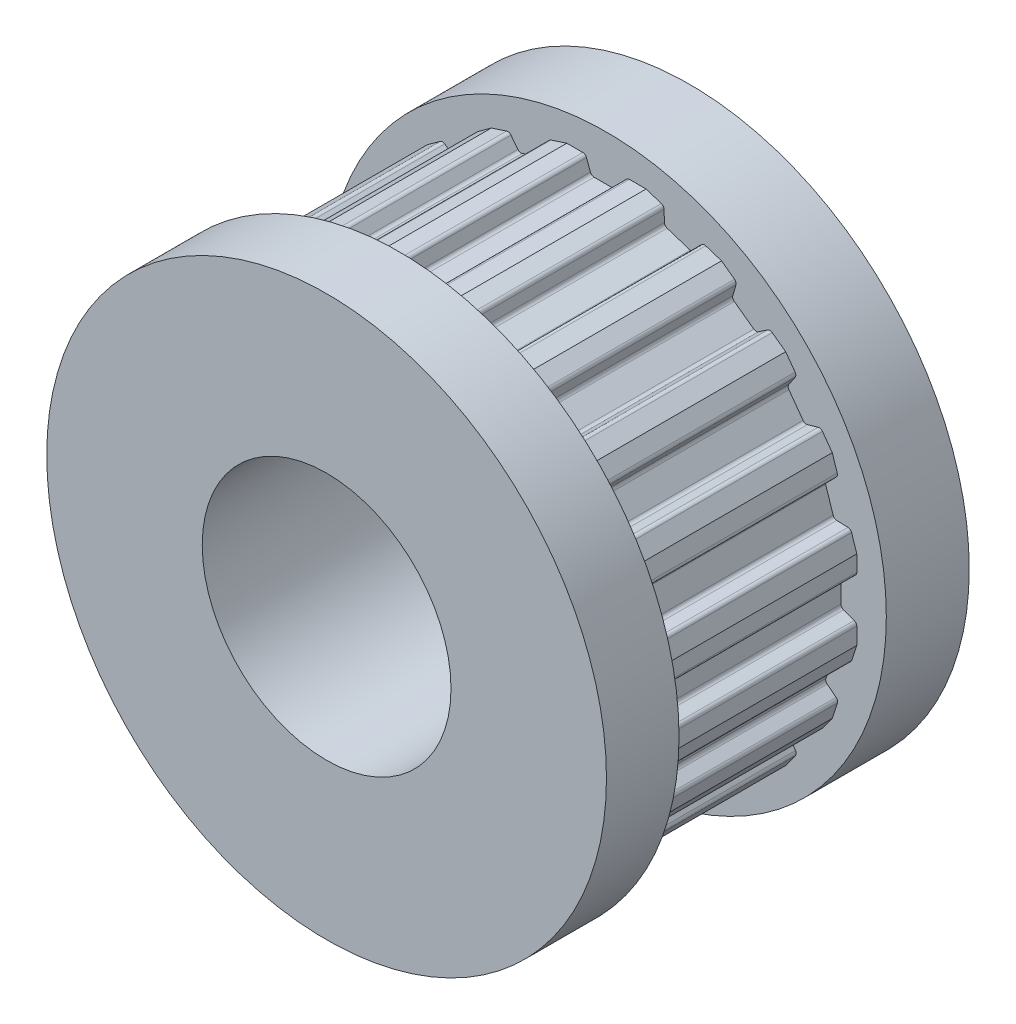
SolidWorks part; units mm, degrees
ref_plane "Front Plane" through (0, 0, 0) normal (0, 0, 1) x (1, 0, 0)
ref_plane "Top Plane" through (0, 0, 0) normal (0, 1, 0) x (1, 0, 0)
ref_plane "Right Plane" through (0, 0, 0) normal (1, 0, 0) x (0, 0, -1)
sketch "Sketch1" plane through (0, 0, 0) normal (0, 0, 1) x (1, 0, 0)
  line L0 (-50.7402, 0.3127) -> (-50.3387, 0.3127)
  line L5 (-50.2492, 0.3754) -> (-50.1561, 0.631)
  line L6 (-50.0666, 0.6937) -> (-49.4855, 0.6937)
  line L7 (-49.7761, 0.6937) -> (-49.7761, 0) construction
  line L8 (-49.3029, 0.3754) -> (-49.396, 0.631)
  line L39 (-51.1727, 0.5191) -> (-51.1822, 0.791)
  line L40 (-50.2492, 0.3754) -> (-49.3029, 0.3754) construction
  line L56 (-49.2134, 0.3127) -> (-48.8278, 0.3127)
  line L60 (-51.8007, 1.0579) -> (-51.248, 0.8783)
  line L61 (-52.0727, 0.8116) -> (-51.9052, 1.0259)
  line L62 (-52.559, 0.9037) -> (-52.1772, 0.7796)
  line L63 (-51.107, 0.4319) -> (-50.7402, 0.3127)
  line L64 (-52.9066, 1.2337) -> (-52.8316, 1.4952)
  line L65 (-53.3373, 1.9401) -> (-52.8672, 1.5985)
  line L66 (-53.6721, 1.7899) -> (-53.4466, 1.942)
  line L67 (-54.1062, 2.0278) -> (-53.7814, 1.7918)
  line L68 (-52.871, 1.1304) -> (-52.559, 0.9037)
  line L69 (-54.3348, 2.449) -> (-54.1827, 2.6746)
  line L70 (-54.5262, 3.254) -> (-54.1846, 2.7838)
  line L71 (-54.891, 3.2146) -> (-54.6295, 3.2895)
  line L72 (-55.2303, 3.575) -> (-54.9943, 3.2501)
  line L73 (-54.3329, 2.3398) -> (-54.1062, 2.0278)
  line L74 (-55.3175, 4.0462) -> (-55.1031, 4.2137)
  line L75 (-55.2508, 4.8709) -> (-55.0712, 4.3182)
  line L76 (-55.6099, 4.9462) -> (-55.338, 4.9367)
  line L77 (-55.8213, 5.3938) -> (-55.6972, 5.0119)
  line L78 (-55.3495, 3.9417) -> (-55.2303, 3.575)
  line L79 (-55.7586, 5.8689) -> (-55.503, 5.962)
  line L80 (-55.4403, 6.6326) -> (-55.4403, 6.0515)
  line L81 (-55.7586, 6.8152) -> (-55.503, 6.7221)
  line L82 (-55.8213, 7.3062) -> (-55.8213, 6.9047)
  line L83 (-55.8213, 5.7794) -> (-55.8213, 5.3938)
  line L84 (-55.6149, 7.7387) -> (-55.343, 7.7482)
  line L85 (-55.0761, 8.3667) -> (-55.2557, 7.814)
  line L86 (-55.3224, 8.6387) -> (-55.1081, 8.4712)
  line L87 (-55.2303, 9.125) -> (-55.3544, 8.7432)
  line L88 (-55.7021, 7.673) -> (-55.8213, 7.3062)
  line L89 (-54.9003, 9.4726) -> (-54.6388, 9.3976)
  line L90 (-54.1939, 9.9033) -> (-54.5355, 9.4332)
  line L91 (-54.3441, 10.2381) -> (-54.192, 10.0126)
  line L92 (-54.1062, 10.6722) -> (-54.3422, 10.3474)
  line L93 (-55.0036, 9.437) -> (-55.2303, 9.125)
  line L94 (-53.685, 10.9008) -> (-53.4594, 10.7487)
  line L95 (-52.88, 11.0922) -> (-53.3502, 10.7506)
  line L96 (-52.9194, 11.457) -> (-52.8445, 11.1955)
  line L97 (-52.559, 11.7963) -> (-52.8839, 11.5603)
  line L98 (-53.7942, 10.8989) -> (-54.1062, 10.6722)
  line L99 (-52.0878, 11.8835) -> (-51.9203, 11.6691)
  line L100 (-51.2631, 11.8168) -> (-51.8158, 11.6372)
  line L101 (-51.1878, 12.1759) -> (-51.1973, 11.904)
  line L102 (-50.7402, 12.3873) -> (-51.1221, 12.2632)
  line L103 (-52.1923, 11.9155) -> (-52.559, 11.7963)
  line L104 (-50.2651, 12.3246) -> (-50.172, 12.069)
  line L105 (-49.5014, 12.0063) -> (-50.0825, 12.0063)
  line L106 (-49.3188, 12.3246) -> (-49.4119, 12.069)
  line L107 (-48.8278, 12.3873) -> (-49.2293, 12.3873)
  line L108 (-50.3546, 12.3873) -> (-50.7402, 12.3873)
  line L109 (-48.3953, 12.1809) -> (-48.3858, 11.909)
  line L110 (-47.7673, 11.6421) -> (-48.32, 11.8217)
  line L111 (-47.4953, 11.8884) -> (-47.6628, 11.6741)
  line L112 (-47.009, 11.7963) -> (-47.3908, 11.9204)
  line L113 (-48.461, 12.2681) -> (-48.8278, 12.3873)
  line L114 (-46.6614, 11.4663) -> (-46.7364, 11.2048)
  line L115 (-46.2307, 10.7599) -> (-46.7008, 11.1015)
  line L116 (-45.8959, 10.9101) -> (-46.1214, 10.758)
  line L117 (-45.4618, 10.6722) -> (-45.7866, 10.9082)
  line L118 (-46.697, 11.5696) -> (-47.009, 11.7963)
  line L119 (-45.2332, 10.251) -> (-45.3853, 10.0254)
  line L120 (-45.0418, 9.446) -> (-45.3834, 9.9162)
  line L121 (-44.677, 9.4854) -> (-44.9385, 9.4105)
  line L122 (-44.3377, 9.125) -> (-44.5737, 9.4499)
  line L123 (-45.2351, 10.3602) -> (-45.4618, 10.6722)
  line L124 (-44.2505, 8.6538) -> (-44.4649, 8.4863)
  line L125 (-44.3172, 7.8291) -> (-44.4968, 8.3818)
  line L126 (-43.9581, 7.7538) -> (-44.23, 7.7633)
  line L127 (-43.7467, 7.3062) -> (-43.8708, 7.6881)
  line L128 (-44.2185, 8.7583) -> (-44.3377, 9.125)
  line L129 (-43.8094, 6.8311) -> (-44.065, 6.738)
  line L130 (-44.1277, 6.0674) -> (-44.1277, 6.6485)
  line L131 (-43.8094, 5.8848) -> (-44.065, 5.9779)
  line L132 (-43.7467, 5.3938) -> (-43.7467, 5.7953)
  line L133 (-43.7467, 6.9206) -> (-43.7467, 7.3062)
  line L134 (-43.9531, 4.9613) -> (-44.225, 4.9518)
  line L135 (-44.4919, 4.3333) -> (-44.3123, 4.886)
  line L136 (-44.2456, 4.0613) -> (-44.4599, 4.2288)
  line L137 (-44.3377, 3.575) -> (-44.2136, 3.9568)
  line L138 (-43.8659, 5.027) -> (-43.7467, 5.3938)
  line L139 (-44.6677, 3.2274) -> (-44.9292, 3.3024)
  line L140 (-45.3741, 2.7967) -> (-45.0325, 3.2668)
  line L141 (-45.2239, 2.4619) -> (-45.376, 2.6874)
  line L142 (-45.4618, 2.0278) -> (-45.2258, 2.3526)
  line L143 (-44.5644, 3.263) -> (-44.3377, 3.575)
  line L144 (-45.883, 1.7992) -> (-46.1086, 1.9513)
  line L145 (-46.688, 1.6078) -> (-46.2178, 1.9494)
  line L146 (-46.6486, 1.243) -> (-46.7235, 1.5045)
  line L147 (-47.009, 0.9037) -> (-46.6841, 1.1397)
  line L148 (-45.7738, 1.8011) -> (-45.4618, 2.0278)
  line L149 (-47.4802, 0.8165) -> (-47.6477, 1.0309)
  line L150 (-48.3049, 0.8832) -> (-47.7522, 1.0628)
  line L151 (-48.3802, 0.5241) -> (-48.3707, 0.796)
  line L152 (-48.8278, 0.3127) -> (-48.4459, 0.4368)
  line L153 (-47.3757, 0.7845) -> (-47.009, 0.9037)
  arc A0 (-50.3387, 0.3127) -> (-50.2492, 0.3754) centre (-50.3387, 0.408) ccw
  arc A1 (-50.1561, 0.631) -> (-50.0666, 0.6937) centre (-50.0666, 0.5985) cw
  arc A2 (-49.396, 0.631) -> (-49.4855, 0.6937) centre (-49.4855, 0.5985) ccw
  arc A3 (-49.2134, 0.3127) -> (-49.3029, 0.3754) centre (-49.2134, 0.408) cw
  arc A4 (-51.107, 0.4319) -> (-51.1727, 0.5191) centre (-51.0775, 0.5225) cw
  arc A5 (-51.1822, 0.791) -> (-51.248, 0.8783) centre (-51.2774, 0.7877) ccw
  arc A6 (-51.9052, 1.0259) -> (-51.8007, 1.0579) centre (-51.8301, 0.9673) cw
  arc A7 (-52.1772, 0.7796) -> (-52.0727, 0.8116) centre (-52.1477, 0.8702) ccw
  arc A8 (-52.871, 1.1304) -> (-52.9066, 1.2337) centre (-52.815, 1.2074) cw
  arc A9 (-52.8316, 1.4952) -> (-52.8672, 1.5985) centre (-52.9232, 1.5214) ccw
  arc A10 (-53.4466, 1.942) -> (-53.3373, 1.9401) centre (-53.3933, 1.863) cw
  arc A11 (-53.7814, 1.7918) -> (-53.6721, 1.7899) centre (-53.7254, 1.8688) ccw
  arc A12 (-54.3329, 2.3398) -> (-54.3348, 2.449) centre (-54.2558, 2.3958) cw
  arc A13 (-54.1827, 2.6746) -> (-54.1846, 2.7838) centre (-54.2616, 2.7278) ccw
  arc A14 (-54.6295, 3.2895) -> (-54.5262, 3.254) centre (-54.6032, 3.198) cw
  arc A15 (-54.9943, 3.2501) -> (-54.891, 3.2146) centre (-54.9172, 3.3061) ccw
  arc A16 (-55.3495, 3.9417) -> (-55.3175, 4.0462) centre (-55.2589, 3.9712) cw
  arc A17 (-55.1031, 4.2137) -> (-55.0712, 4.3182) centre (-55.1618, 4.2888) ccw
  arc A18 (-55.338, 4.9367) -> (-55.2508, 4.8709) centre (-55.3414, 4.8415) cw
  arc A19 (-55.6972, 5.0119) -> (-55.6099, 4.9462) centre (-55.6066, 5.0414) ccw
  arc A20 (-55.8213, 5.7794) -> (-55.7586, 5.8689) centre (-55.726, 5.7794) cw
  arc A21 (-55.503, 5.962) -> (-55.4403, 6.0515) centre (-55.5355, 6.0515) ccw
  arc A22 (-55.503, 6.7221) -> (-55.4403, 6.6326) centre (-55.5355, 6.6326) cw
  arc A23 (-55.8213, 6.9047) -> (-55.7586, 6.8152) centre (-55.726, 6.9047) ccw
  arc A24 (-55.7021, 7.673) -> (-55.6149, 7.7387) centre (-55.6115, 7.6435) cw
  arc A25 (-55.343, 7.7482) -> (-55.2557, 7.814) centre (-55.3463, 7.8434) ccw
  arc A26 (-55.1081, 8.4712) -> (-55.0761, 8.3667) centre (-55.1667, 8.3961) cw
  arc A27 (-55.3544, 8.7432) -> (-55.3224, 8.6387) centre (-55.2638, 8.7137) ccw
  arc A28 (-55.0036, 9.437) -> (-54.9003, 9.4726) centre (-54.9266, 9.381) cw
  arc A29 (-54.6388, 9.3976) -> (-54.5355, 9.4332) centre (-54.6126, 9.4892) ccw
  arc A30 (-54.192, 10.0126) -> (-54.1939, 9.9033) centre (-54.271, 9.9593) cw
  arc A31 (-54.3422, 10.3474) -> (-54.3441, 10.2381) centre (-54.2652, 10.2914) ccw
  arc A32 (-53.7942, 10.8989) -> (-53.685, 10.9008) centre (-53.7382, 10.8218) cw
  arc A33 (-53.4594, 10.7487) -> (-53.3502, 10.7506) centre (-53.4062, 10.8276) ccw
  arc A34 (-52.8445, 11.1955) -> (-52.88, 11.0922) centre (-52.936, 11.1692) cw
  arc A35 (-52.8839, 11.5603) -> (-52.9194, 11.457) centre (-52.8279, 11.4832) ccw
  arc A36 (-52.1923, 11.9155) -> (-52.0878, 11.8835) centre (-52.1628, 11.8249) cw
  arc A37 (-51.9203, 11.6691) -> (-51.8158, 11.6372) centre (-51.8452, 11.7278) ccw
  arc A38 (-51.1973, 11.904) -> (-51.2631, 11.8168) centre (-51.2925, 11.9074) cw
  arc A39 (-51.1221, 12.2632) -> (-51.1878, 12.1759) centre (-51.0926, 12.1726) ccw
  arc A40 (-50.3546, 12.3873) -> (-50.2651, 12.3246) centre (-50.3546, 12.292) cw
  arc A41 (-50.172, 12.069) -> (-50.0825, 12.0063) centre (-50.0825, 12.1015) ccw
  arc A42 (-49.4119, 12.069) -> (-49.5014, 12.0063) centre (-49.5014, 12.1015) cw
  arc A43 (-49.2293, 12.3873) -> (-49.3188, 12.3246) centre (-49.2293, 12.292) ccw
  arc A44 (-48.461, 12.2681) -> (-48.3953, 12.1809) centre (-48.4905, 12.1775) cw
  arc A45 (-48.3858, 11.909) -> (-48.32, 11.8217) centre (-48.2906, 11.9123) ccw
  arc A46 (-47.6628, 11.6741) -> (-47.7673, 11.6421) centre (-47.7379, 11.7327) cw
  arc A47 (-47.3908, 11.9204) -> (-47.4953, 11.8884) centre (-47.4203, 11.8298) ccw
  arc A48 (-46.697, 11.5696) -> (-46.6614, 11.4663) centre (-46.753, 11.4926) cw
  arc A49 (-46.7364, 11.2048) -> (-46.7008, 11.1015) centre (-46.6448, 11.1786) ccw
  arc A50 (-46.1214, 10.758) -> (-46.2307, 10.7599) centre (-46.1747, 10.837) cw
  arc A51 (-45.7866, 10.9082) -> (-45.8959, 10.9101) centre (-45.8426, 10.8312) ccw
  arc A52 (-45.2351, 10.3602) -> (-45.2332, 10.251) centre (-45.3122, 10.3042) cw
  arc A53 (-45.3853, 10.0254) -> (-45.3834, 9.9162) centre (-45.3064, 9.9722) ccw
  arc A54 (-44.9385, 9.4105) -> (-45.0418, 9.446) centre (-44.9648, 9.502) cw
  arc A55 (-44.5737, 9.4499) -> (-44.677, 9.4854) centre (-44.6508, 9.3939) ccw
  arc A56 (-44.2185, 8.7583) -> (-44.2505, 8.6538) centre (-44.3091, 8.7288) cw
  arc A57 (-44.4649, 8.4863) -> (-44.4968, 8.3818) centre (-44.4062, 8.4112) ccw
  arc A58 (-44.23, 7.7633) -> (-44.3172, 7.8291) centre (-44.2266, 7.8585) cw
  arc A59 (-43.8708, 7.6881) -> (-43.9581, 7.7538) centre (-43.9614, 7.6586) ccw
  arc A60 (-43.7467, 6.9206) -> (-43.8094, 6.8311) centre (-43.842, 6.9206) cw
  arc A61 (-44.065, 6.738) -> (-44.1277, 6.6485) centre (-44.0325, 6.6485) ccw
  arc A62 (-44.065, 5.9779) -> (-44.1277, 6.0674) centre (-44.0325, 6.0674) cw
  arc A63 (-43.7467, 5.7953) -> (-43.8094, 5.8848) centre (-43.842, 5.7953) ccw
  arc A64 (-43.8659, 5.027) -> (-43.9531, 4.9613) centre (-43.9565, 5.0565) cw
  arc A65 (-44.225, 4.9518) -> (-44.3123, 4.886) centre (-44.2217, 4.8566) ccw
  arc A66 (-44.4599, 4.2288) -> (-44.4919, 4.3333) centre (-44.4013, 4.3039) cw
  arc A67 (-44.2136, 3.9568) -> (-44.2456, 4.0613) centre (-44.3042, 3.9863) ccw
  arc A68 (-44.5644, 3.263) -> (-44.6677, 3.2274) centre (-44.6414, 3.319) cw
  arc A69 (-44.9292, 3.3024) -> (-45.0325, 3.2668) centre (-44.9554, 3.2108) ccw
  arc A70 (-45.376, 2.6874) -> (-45.3741, 2.7967) centre (-45.297, 2.7407) cw
  arc A71 (-45.2258, 2.3526) -> (-45.2239, 2.4619) centre (-45.3028, 2.4086) ccw
  arc A72 (-45.7738, 1.8011) -> (-45.883, 1.7992) centre (-45.8298, 1.8782) cw
  arc A73 (-46.1086, 1.9513) -> (-46.2178, 1.9494) centre (-46.1618, 1.8724) ccw
  arc A74 (-46.7235, 1.5045) -> (-46.688, 1.6078) centre (-46.632, 1.5308) cw
  arc A75 (-46.6841, 1.1397) -> (-46.6486, 1.243) centre (-46.7401, 1.2168) ccw
  arc A76 (-47.3757, 0.7845) -> (-47.4802, 0.8165) centre (-47.4052, 0.8751) cw
  arc A77 (-47.6477, 1.0309) -> (-47.7522, 1.0628) centre (-47.7228, 0.9722) ccw
  arc A78 (-48.3707, 0.796) -> (-48.3049, 0.8832) centre (-48.2755, 0.7926) cw
  arc A79 (-48.4459, 0.4368) -> (-48.3802, 0.5241) centre (-48.4754, 0.5274) ccw
  point P1 (-50.2841, 0.3299)
  point P2 (-49.784, 6.35)
  point P3 (0, 0)
  point P7 (-49.2681, 0.3299)
  point P26 (0, 0)
  point P247 (0, 0)
  point P570 (-49.784, 6.35)
  dimension "D1" = 0.0953
  dimension "D2" = 20
  dimension "D3" = 40
  dimension "D4" = 1.016
  dimension "D7" = 0.381
sketch "Sketch2" plane through (0, 0, 0) normal (0, 0, 1) x (1, 0, 0)
  point P0 (-49.784, 12.7)
extrude "Boss-Extrude1" add sketch "Sketch1" along normal blind 5
sketch "Sketch3" plane through (0, 0, 5) normal (0, 0, 1) x (1, 0, 0)
  circle A0 centre (-49.784, 6.35) radius 6.75
  point P3 (0, 0)
  point P4 (-49.784, 12.7)
  point P5 (-49.784, 12.7)
  point P6 (-49.784, 12.7)
extrude "Boss-Extrude2" add sketch "Sketch3" along normal blind 1.75
sketch "Sketch5" plane through (0, 0, 0) normal (0, 0, -1) x (-1, 0, 0)
  circle A0 centre (49.784, 6.35) radius 6.75
extrude "Boss-Extrude3" add sketch "Sketch5" along normal blind 2
sketch "Sketch6" plane through (0, 0, -2) normal (0, 0, -1) x (-1, 0, 0)
  circle A0 centre (49.784, 6.35) radius 3
  point P0 (49.784, 6.35)
extrude "Cut-Extrude1" cut sketch "Sketch6" against normal through all
